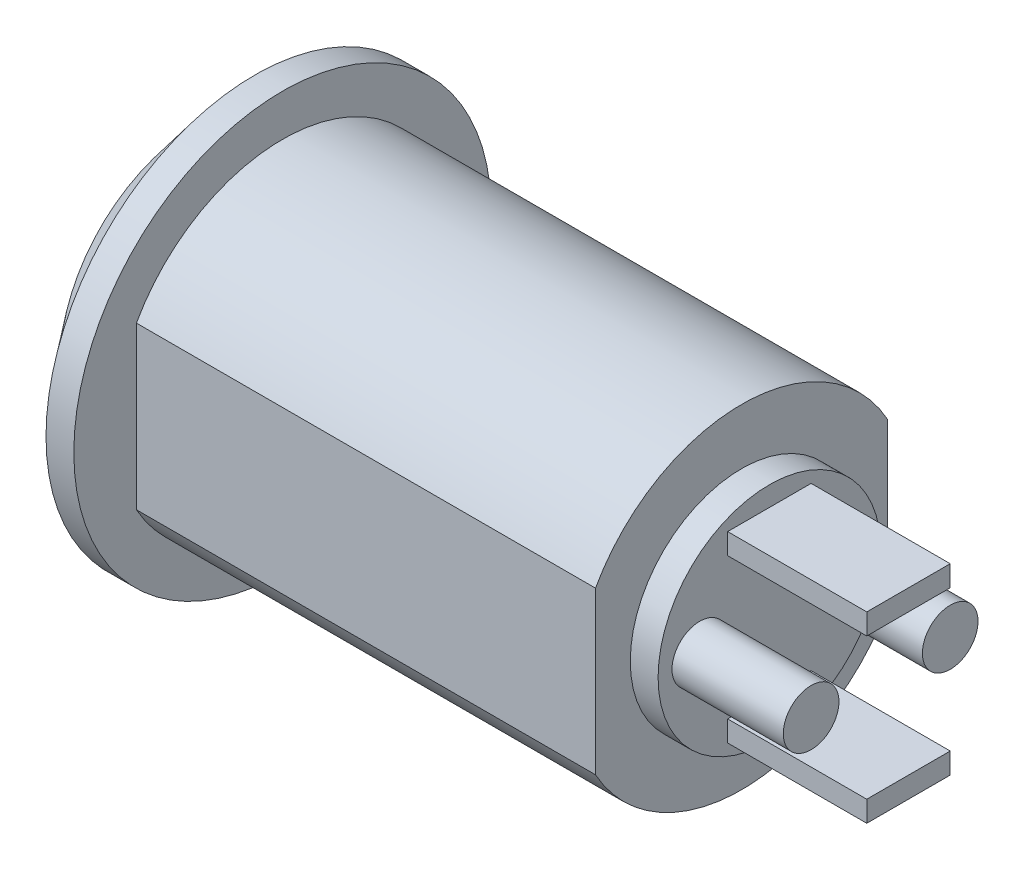
SolidWorks part; units mm, degrees
ref_plane "前视基准面" through (0, 0, 0) normal (0, 0, 1) x (1, 0, 0)
ref_plane "上视基准面" through (0, 0, 0) normal (0, 1, 0) x (1, 0, 0)
ref_plane "右视基准面" through (0, 0, 0) normal (1, 0, 0) x (0, 0, -1)
sketch "草图1" plane through (0, 0, 0) normal (0, 0, 1) x (1, 0, 0)
  line L0 (0, 0) -> (25.1904, 0) construction
  line L1 (0, 0) -> (0, 5)
  line L2 (0, 5) -> (2, 7.5)
  line L3 (2, 7.5) -> (3, 7.5)
  line L4 (3, 7.5) -> (3, 6)
  line L5 (3, 6) -> (19.5, 6)
  line L6 (19.5, 6) -> (19.5, 4)
  line L7 (19.5, 4) -> (20.5, 4)
  line L8 (20.5, 4) -> (20.5, 0)
  line L9 (0, 0) -> (20.5, 0)
  dimension "D1" = 3
  dimension "D2" = 16.5
  dimension "D3" = 1
  dimension "D4" = 6
  dimension "D5" = 7.5
  dimension "D6" = 5
  dimension "D7" = 2
  dimension "D8" = 4
revolve "旋转1" add sketch "草图1" angle 360 about L0
sketch "草图2" plane through (0, 0, 0) normal (1, 0, 0) x (0, 0, -1)
  line L0 (3.341, 0) -> (-2.9465, 0) construction
  line L1 (1, 3.25) -> (-1, 3.25)
  line L2 (1, 3.25) -> (1, -3.25)
  line L3 (1, -3.25) -> (-1, -3.25)
  line L4 (-1, 3.25) -> (-1, -3.25)
  line L5 (0, 3.7355) -> (0, -4.6232) construction
  dimension "D1" = 2
  dimension "D2" = 6.5
extrude "切除-拉伸1" cut sketch "草图2" along normal blind 10
sketch "草图3" plane through (20.5, 0, 0) normal (1, 0, 0) x (0, 0, -1)
  line L0 (0, 12.0791) -> (0, -13.3573) construction
  line L1 (-11.0019, 9.8635) -> (-5.25, 9.8635)
  line L2 (-11.0019, 9.8635) -> (-11.0019, -8.5853)
  line L3 (-11.0019, -8.5853) -> (-5.25, -8.5853)
  line L4 (-5.25, 9.8635) -> (-5.25, -8.5853)
  line L5 (5.25, 9.8635) -> (5.25, -8.5853)
  line L6 (11.0019, -8.5853) -> (5.25, -8.5853)
  line L7 (11.0019, 9.8635) -> (11.0019, -8.5853)
  line L8 (11.0019, 9.8635) -> (5.25, 9.8635)
  dimension "D1" = 10.5
extrude "切除-拉伸2" cut sketch "草图3" against normal up to surface (17.5 mm away) up to face at (3, 0, 7.5)
sketch "草图4" plane through (20.5, 0, 0) normal (1, 0, 0) x (0, 0, -1)
  line L0 (-9.5052, 0) -> (9.9737, 0) construction
  line L1 (0, 7.9765) -> (0, -8.5189) construction
  line L2 (-1.5, 3.29) -> (1.5, 3.29)
  line L3 (-1.5, 3.29) -> (-1.5, 2.54)
  line L4 (-1.5, 2.54) -> (1.5, 2.54)
  line L5 (1.5, 3.29) -> (1.5, 2.54)
  line L6 (1.5, -3.29) -> (1.5, -2.54)
  line L7 (-1.5, -2.54) -> (1.5, -2.54)
  line L8 (-1.5, -3.29) -> (-1.5, -2.54)
  line L9 (-1.5, -3.29) -> (1.5, -3.29)
  dimension "D1" = 0.75
  dimension "D2" = 3
  dimension "D3" = 5.08
extrude "方形封装" add sketch "草图4" along normal blind 5
fillet "圆角1" [suppressed] radius 1
sketch "草图5" plane through (20.5, 0, 0) normal (1, 0, 0) x (0, 0, -1)
  line L0 (-9.0292, 0) -> (9.9654, 0) construction
  line L1 (0, 8.0438) -> (0, -8.4872) construction
  circle A0 centre (-2.5, 0) radius 1
  circle A1 centre (2.5, 0) radius 1
  dimension "D1" = 2
  dimension "D2" = 5
extrude "凸台-拉伸1" add sketch "草图5" along normal blind 4
